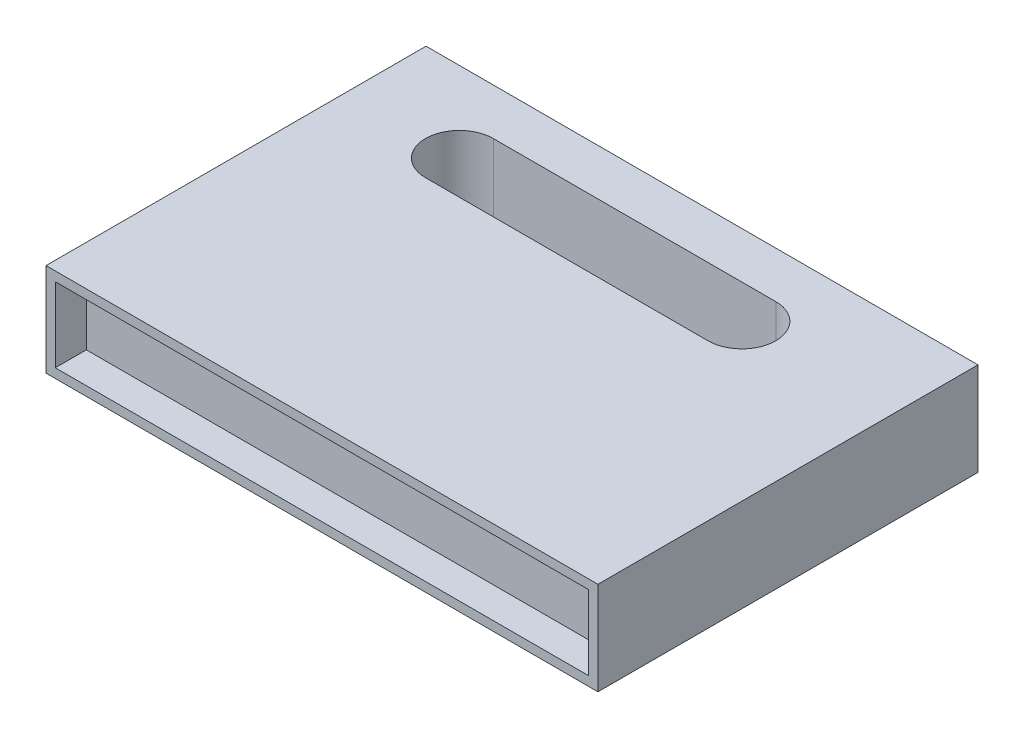
SolidWorks part; units mm, degrees
material "AISI 1020"
ref_plane "Front Plane" through (0, 0, 0) normal (0, 0, 1) x (1, 0, 0)
ref_plane "Top Plane" through (0, 0, 0) normal (0, 1, 0) x (1, 0, 0)
ref_plane "Right Plane" through (0, 0, 0) normal (1, 0, 0) x (0, 0, -1)
sketch "Sketch1" plane through (0, 0, 0) normal (0, 1, 0) x (1, 0, 0)
  line L1 (-88.8655, -61.1881) -> (88.8655, -61.1881)
  line L2 (-88.8655, -61.1881) -> (-88.8655, 61.1881)
  line L3 (-88.8655, 61.1881) -> (88.8655, 61.1881)
  line L4 (88.8655, -61.1881) -> (88.8655, 61.1881)
  line L5 (-88.8655, -61.1881) -> (88.8655, 61.1881) construction
  line L6 (-88.8655, 61.1881) -> (88.8655, -61.1881) construction
  point P0 (0, 0)
extrude "Boss-Extrude1" add sketch "Sketch1" along normal blind 30
sketch "Sketch2" plane through (0, 0, 61.1881) normal (0, 0, 1) x (1, 0, 0)
  line L8 (-85.8655, 3) -> (85.8655, 3)
  line L9 (85.8655, 3) -> (85.8655, 27)
  line L10 (85.8655, 27) -> (-85.8655, 27)
  line L11 (-85.8655, 27) -> (-85.8655, 3)
  line L12 (-85.8655, 3) -> (85.8655, 3)
  line L13 (85.8655, 3) -> (85.8655, 27)
  line L14 (85.8655, 27) -> (-85.8655, 27)
  line L15 (-85.8655, 27) -> (-85.8655, 3)
  dimension "D1" = 3
extrude "Cut-Extrude1" cut sketch "Sketch2" against normal blind 10
sketch "Sketch3" plane through (0, 30, 0) normal (0, 1, 0) x (1, 0, 0)
  line L0 (-52.2914, 35.3398) -> (38.6918, 35.3398) construction
  line L1 (-52.2914, 46.2578) -> (38.6918, 46.2578)
  line L2 (-52.2914, 24.4218) -> (38.6918, 24.4218)
  arc A0 (-52.2914, 46.2578) -> (-52.2914, 24.4218) centre (-52.2914, 35.3398) ccw
  arc A1 (38.6918, 24.4218) -> (38.6918, 46.2578) centre (38.6918, 35.3398) ccw
  point P2 (-6.7998, 35.3398)
extrude "Cut-Extrude2" cut sketch "Sketch3" against normal through all
